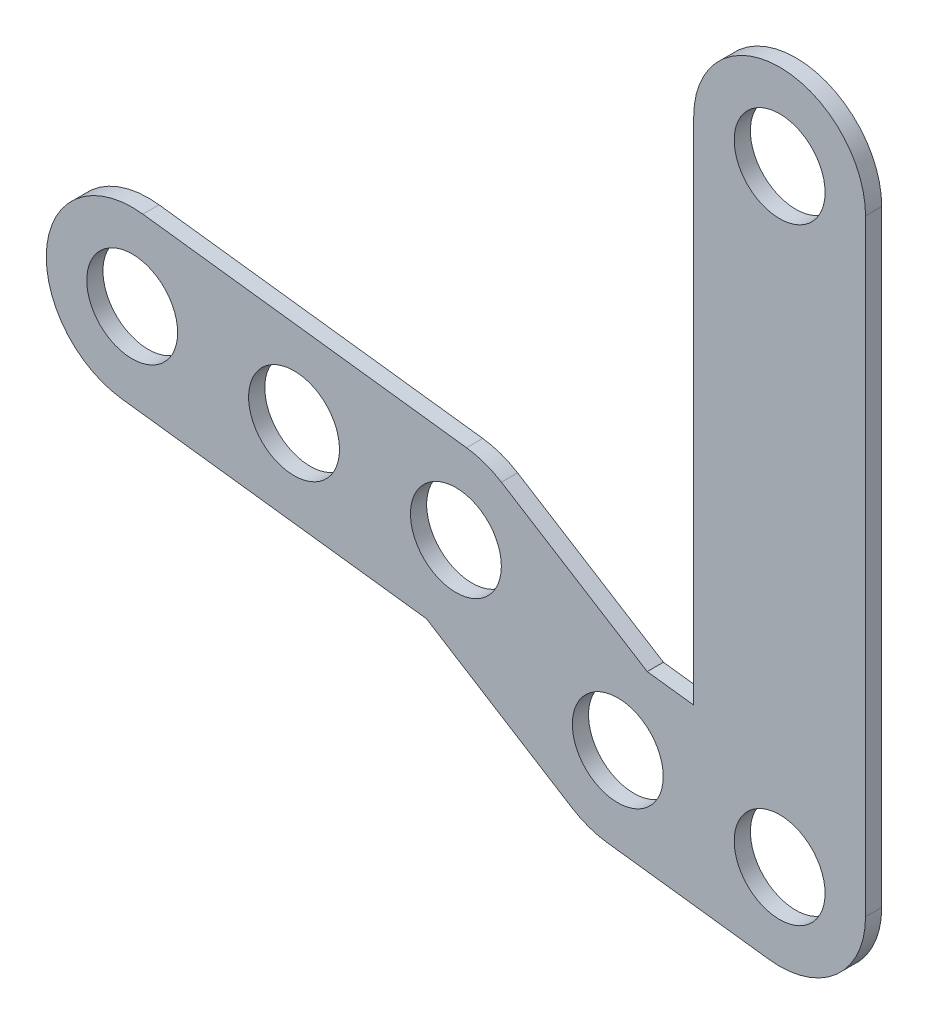
SolidWorks part; units mm, degrees
ref_plane "Front Plane" through (0, 0, 0) normal (0, 0, 1) x (1, 0, 0)
ref_plane "Top Plane" through (0, 0, 0) normal (0, 1, 0) x (1, 0, 0)
ref_plane "Right Plane" through (0, 0, 0) normal (1, 0, 0) x (0, 0, -1)
sketch "Model" plane through (0, 0, 0) normal (0, 0, 1) x (1, 0, 0)
  line L0 (293.6621, 222.25) -> (293.6621, 31.75)
  line L1 (239.7379, 222.25) -> (239.7379, 62.2922)
  line L2 (225.1461, 64.1162) -> (239.7379, 62.2922)
  line L3 (179.3899, 92.7138) -> (225.1461, 64.1162)
  line L4 (66.8442, 109.3039) -> (168.4442, 96.6039)
  line L5 (60.1558, 55.7961) -> (155.8539, 43.8338)
  line L6 (155.8539, 43.8338) -> (201.6101, 15.2362)
  line L7 (212.5558, 11.3461) -> (263.3558, 4.9961)
  circle A0 centre (63.5, 82.55) radius 14.2621
  circle A1 centre (114.3, 76.2) radius 14.2621
  circle A2 centre (165.1, 69.85) radius 14.2621
  circle A3 centre (215.9, 38.1) radius 14.2621
  circle A4 centre (266.7, 222.25) radius 14.2621
  circle A5 centre (266.7, 31.75) radius 14.2621
  arc A6 (263.3558, 4.9961) -> (293.6621, 31.75) centre (266.7, 31.75) ccw
  arc A7 (293.6621, 222.25) -> (239.7379, 222.25) centre (266.7, 222.25) ccw
  arc A8 (179.3899, 92.7138) -> (168.4442, 96.6039) centre (165.1, 69.85) ccw
  arc A9 (66.8442, 109.3039) -> (60.1558, 55.7961) centre (63.5, 82.55) ccw
  arc A10 (201.6101, 15.2362) -> (212.5558, 11.3461) centre (215.9, 38.1) ccw
extrude "Boss-Extrude1" add sketch "Model" along normal blind 5.08
